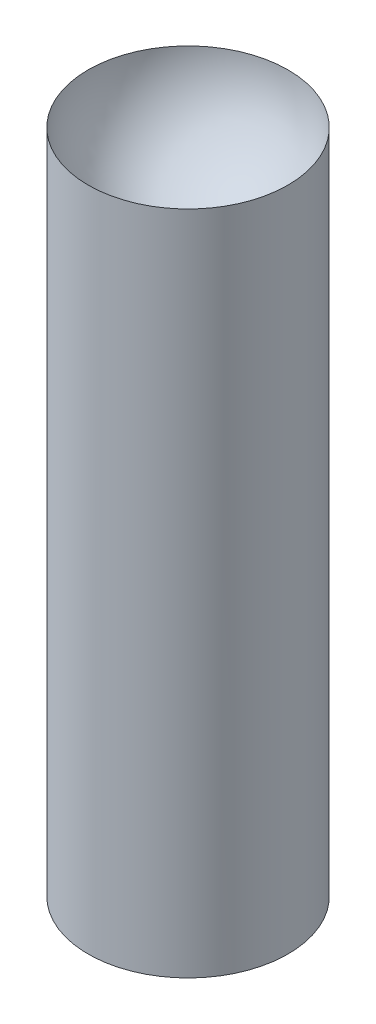
SolidWorks part; units mm, degrees
ref_plane "Front Plane" through (0, 0, 0) normal (0, 0, 1) x (1, 0, 0)
ref_plane "Top Plane" through (0, 0, 0) normal (0, 1, 0) x (1, 0, 0)
ref_plane "Right Plane" through (0, 0, 0) normal (1, 0, 0) x (0, 0, -1)
sketch "Sketch1" plane through (0, 0, 0) normal (0, 1, 0) x (1, 0, 0)
  circle A0 centre (0, 0) radius 11.43
extrude "Boss-Extrude1" add sketch "Sketch1" along normal blind 76.2
sketch "Sketch3" plane through (0, 76.2, 0) normal (0, 1, 0) x (1, 0, 0)
  line L0 (0, 11.43) -> (0, -11.43)
  line L1 (0, 11.43) -> (0, -11.43) construction
  arc A0 (0, -11.43) -> (0, 11.43) centre (0, 0) ccw
revolve "Cut-Revolve1" cut sketch "Sketch3" angle 360 about L1
